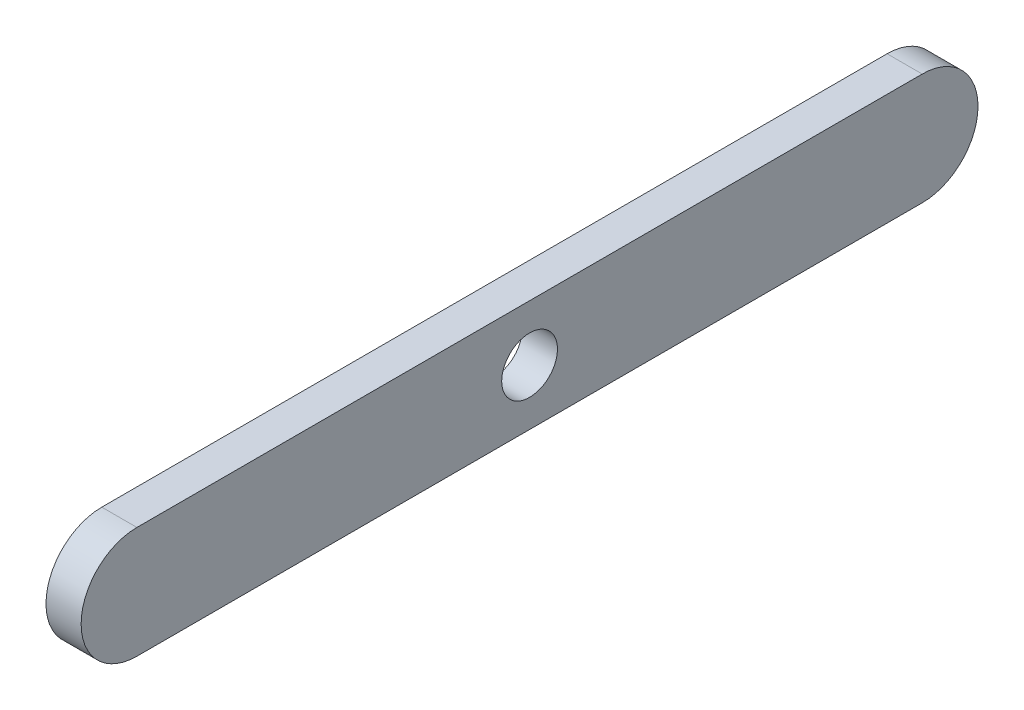
SolidWorks part; units mm, degrees
ref_plane "Front Plane" through (0, 0, 0) normal (0, 0, 1) x (1, 0, 0)
ref_plane "Top Plane" through (0, 0, 0) normal (0, 1, 0) x (1, 0, 0)
ref_plane "Right Plane" through (0, 0, 0) normal (1, 0, 0) x (0, 0, -1)
sketch "Sketch1" plane through (0, 0, 0) normal (1, 0, 0) x (0, 0, -1)
  line L0 (33.525, 0) -> (-11.175, 0)
  line L1 (11.175, 3.175) -> (11.175, 10.7672) construction
  line L5 (33.525, 6.35) -> (-11.175, 6.35)
  circle A0 centre (11.175, 3.175) radius 1.5875
  arc A1 (-11.175, 6.35) -> (-11.175, 0) centre (-11.175, 3.175) ccw
  arc A2 (33.525, 6.35) -> (33.525, 0) centre (33.525, 3.175) cw
extrude "Boss-Extrude1" add sketch "Sketch1" along normal blind 2
